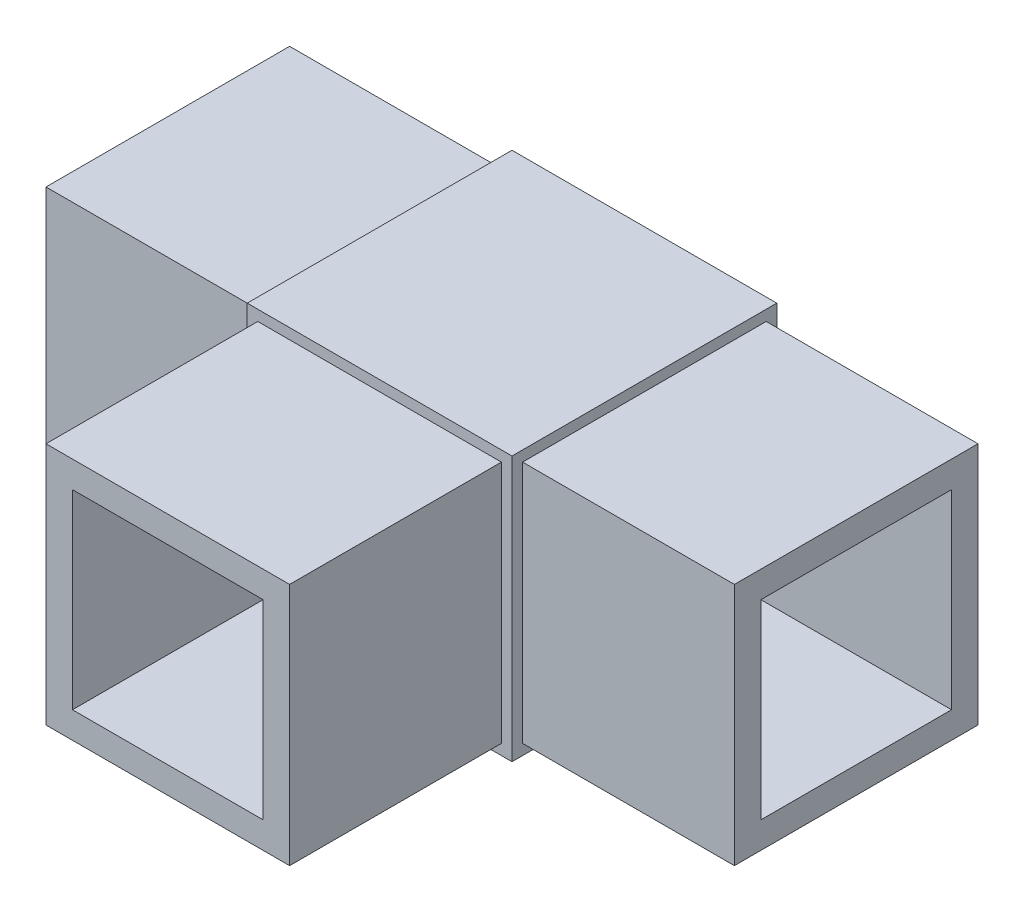
SolidWorks part; units mm, degrees
ref_plane "Front Plane" through (0, 0, 0) normal (0, 0, 1) x (1, 0, 0)
ref_plane "Top Plane" through (0, 0, 0) normal (0, 1, 0) x (1, 0, 0)
ref_plane "Right Plane" through (0, 0, 0) normal (1, 0, 0) x (0, 0, -1)
sketch "Sketch1" plane through (0, 0, 0) normal (0, 0, 1) x (1, 0, 0)
  line L1 (109.1192, -209.4699) -> (174.1192, -209.4699)
  line L2 (109.1192, -209.4699) -> (109.1192, -184.4699)
  line L3 (109.1192, -184.4699) -> (174.1192, -184.4699)
  line L4 (174.1192, -209.4699) -> (174.1192, -184.4699)
  dimension "D1" = 25
  dimension "D2" = 65
extrude "Boss-Extrude1" add sketch "Sketch1" along normal blind 25 contours L1 L4 L3 L2
sketch "Sketch2" plane through (0, 0, 25) normal (0, 0, 1) x (1, 0, 0)
  line L0 (109.1192, -209.4699) -> (174.1192, -209.4699) construction
  line L1 (129.1192, -209.4699) -> (154.1192, -209.4699)
  line L2 (129.1192, -209.4699) -> (129.1192, -184.4699)
  line L3 (129.1192, -184.4699) -> (154.1192, -184.4699)
  line L4 (154.1192, -209.4699) -> (154.1192, -184.4699)
  line L5 (109.1192, -184.4699) -> (174.1192, -184.4699) construction
  line L6 (109.1192, -209.4699) -> (109.1192, -184.4699) construction
  dimension "D1" = 25
  dimension "D2" = 20
extrude "Boss-Extrude2" add sketch "Sketch2" along normal blind 20 contours L2 L3 L4 L1
sketch "Sketch3" plane through (0, 0, 45) normal (0, 0, 1) x (1, 0, 0)
  line L1 (129.1192, -209.4699) -> (154.1192, -209.4699)
  line L2 (129.1192, -209.4699) -> (129.1192, -184.4699)
  line L3 (129.1192, -184.4699) -> (154.1192, -184.4699)
  line L4 (154.1192, -209.4699) -> (154.1192, -184.4699)
  line L5 (130.1192, -208.4699) -> (153.1192, -208.4699)
  line L6 (130.1192, -208.4699) -> (130.1192, -185.4699)
  line L7 (130.1192, -185.4699) -> (153.1192, -185.4699)
  line L8 (153.1192, -208.4699) -> (153.1192, -185.4699)
  dimension "D1" = 1
  dimension "D2" = 1
  dimension "D3" = 1
  dimension "D4" = 1
extrude "Cut-Extrude2" cut sketch "Sketch3" against normal blind 20
sketch "Sketch4" plane through (109.1192, 0, 0) normal (-1, 0, 0) x (0, 0, 1)
  line L0 (25, -209.4699) -> (25, -184.4699) construction
  line L1 (0, -209.4699) -> (25, -209.4699)
  line L2 (0, -209.4699) -> (0, -184.4699)
  line L3 (0, -184.4699) -> (25, -184.4699)
  line L4 (25, -209.4699) -> (25, -184.4699)
  line L6 (1, -208.4699) -> (24, -208.4699)
  line L7 (1, -208.4699) -> (1, -185.4699)
  line L8 (1, -185.4699) -> (24, -185.4699)
  line L9 (24, -208.4699) -> (24, -185.4699)
  dimension "D1" = 1
  dimension "D2" = 1
  dimension "D3" = 1
  dimension "D4" = 1
extrude "Cut-Extrude3" cut sketch "Sketch4" against normal blind 20
sketch "Sketch5" plane through (174.1192, 0, 0) normal (1, 0, 0) x (0, 0, -1)
  line L1 (0, -209.4699) -> (-25, -209.4699)
  line L2 (0, -209.4699) -> (0, -184.4699)
  line L3 (0, -184.4699) -> (-25, -184.4699)
  line L4 (-25, -209.4699) -> (-25, -184.4699)
  line L5 (-1, -208.4699) -> (-24, -208.4699)
  line L6 (-1, -208.4699) -> (-1, -185.4699)
  line L7 (-1, -185.4699) -> (-24, -185.4699)
  line L8 (-24, -208.4699) -> (-24, -185.4699)
  dimension "D1" = 1
  dimension "D2" = 1
  dimension "D3" = 1
  dimension "D4" = 1
extrude "Cut-Extrude4" cut sketch "Sketch5" against normal blind 20
sketch "Sketch6" plane through (174.1192, 0, 0) normal (1, 0, 0) x (0, 0, -1)
  line L0 (-24, -208.4699) -> (-1, -208.4699) construction
  line L1 (-3.5, -205.9699) -> (-21.5, -205.9699)
  line L2 (-3.5, -205.9699) -> (-3.5, -187.9699)
  line L3 (-3.5, -187.9699) -> (-21.5, -187.9699)
  line L4 (-21.5, -205.9699) -> (-21.5, -187.9699)
  line L5 (-1, -208.4699) -> (-1, -185.4699) construction
  line L6 (-1, -185.4699) -> (-24, -185.4699) construction
  line L7 (-24, -185.4699) -> (-24, -208.4699) construction
  dimension "D1" = 2.5
  dimension "D2" = 2.5
  dimension "D3" = 2.5
  dimension "D4" = 2.5
extrude "Cut-Extrude5" cut sketch "Sketch6" against normal through all
sketch "Sketch7" plane through (0, 0, 45) normal (0, 0, 1) x (1, 0, 0)
  line L0 (130.1192, -208.4699) -> (153.1192, -208.4699) construction
  line L1 (150.6192, -205.9699) -> (132.6192, -205.9699)
  line L2 (150.6192, -205.9699) -> (150.6192, -187.9699)
  line L3 (150.6192, -187.9699) -> (132.6192, -187.9699)
  line L4 (132.6192, -205.9699) -> (132.6192, -187.9699)
  line L5 (153.1192, -185.4699) -> (130.1192, -185.4699) construction
  line L6 (153.1192, -208.4699) -> (153.1192, -185.4699) construction
  line L7 (130.1192, -185.4699) -> (130.1192, -208.4699) construction
  dimension "D1" = 2.5
  dimension "D2" = 2.5
  dimension "D3" = 2.5
  dimension "D4" = 2.5
extrude "Cut-Extrude6" cut sketch "Sketch7" against normal up to surface (41.5 mm away) up to face at (141.6192, -196.9699, 3.5)
